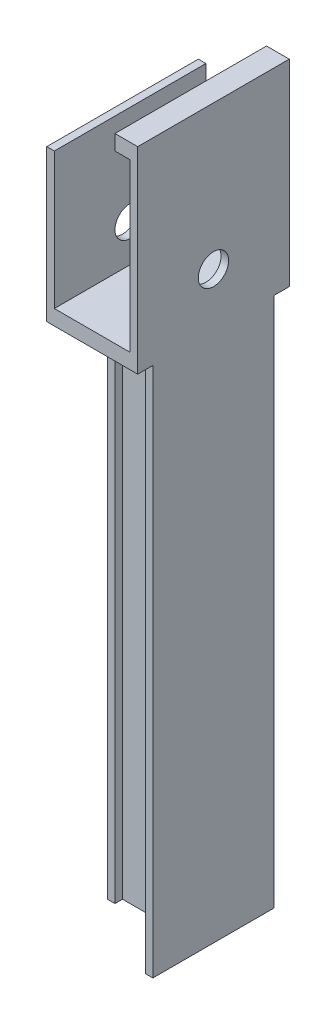
SolidWorks part; units mm, degrees
ref_plane "Front Plane" through (0, 0, 0) normal (0, 0, 1) x (1, 0, 0)
ref_plane "Top Plane" through (0, 0, 0) normal (0, 1, 0) x (1, 0, 0)
ref_plane "Right Plane" through (0, 0, 0) normal (1, 0, 0) x (0, 0, -1)
sketch "Sketch1" plane through (0, 0, 0) normal (0, 1, 0) x (1, 0, 0)
  line L1 (-130.7317, 99.2683) -> (-70.7317, 99.2683)
  line L2 (-130.7317, 99.2683) -> (-130.7317, -0.7317)
  line L3 (-130.7317, -0.7317) -> (-70.7317, -0.7317)
  line L4 (-70.7317, 99.2683) -> (-70.7317, -0.7317)
  dimension "D1" = 60
  dimension "D2" = 100
extrude "Boss-Extrude1" add sketch "Sketch1" along normal blind 100
sketch "Sketch2" plane through (0, 100, 0) normal (0, 1, 0) x (1, 0, 0)
  line L0 (-70.7317, 99.2683) -> (-130.7317, 99.2683) construction
  line L1 (-125.7317, 99.2683) -> (-75.7317, 99.2683)
  line L2 (-125.7317, 99.2683) -> (-125.7317, -0.7317)
  line L3 (-125.7317, -0.7317) -> (-75.7317, -0.7317)
  line L4 (-75.7317, 99.2683) -> (-75.7317, -0.7317)
  line L5 (-130.7317, -0.7317) -> (-70.7317, -0.7317) construction
  dimension "D1" = 50
  dimension "D2" = 5
extrude "Cut-Extrude1" cut sketch "Sketch2" against normal blind 40
sketch "Sketch3" plane through (0, 100, 0) normal (0, 1, 0) x (1, 0, 0)
  line L1 (-75.7317, 99.2683) -> (-70.7317, 99.2683)
  line L2 (-75.7317, 99.2683) -> (-75.7317, -0.7317)
  line L3 (-75.7317, -0.7317) -> (-70.7317, -0.7317)
  line L4 (-70.7317, 99.2683) -> (-70.7317, -0.7317)
extrude "Boss-Extrude2" add sketch "Sketch3" along normal blind 30
sketch "Sketch4" plane through (-75.7317, 0, 0) normal (-1, 0, 0) x (0, 0, 1)
  line L0 (0.7317, 60) -> (0.7317, 130) construction
  line L1 (-99.2683, 130) -> (0.7317, 130)
  line L2 (-99.2683, 130) -> (-99.2683, 120)
  line L3 (-99.2683, 120) -> (0.7317, 120)
  line L4 (0.7317, 130) -> (0.7317, 120)
  dimension "D1" = 10
extrude "Boss-Extrude3" add sketch "Sketch4" along normal blind 10
sketch "Sketch5" plane through (0, 0, 0) normal (0, -1, 0) x (-1, 0, 0)
  line L6 (70.7317, -0.7317) -> (70.7317, 99.2683) construction
  line L7 (70.7317, 89.2683) -> (130.7317, 89.2683)
  line L8 (70.7317, 89.2683) -> (70.7317, 9.2683)
  line L9 (70.7317, 9.2683) -> (130.7317, 9.2683)
  line L10 (130.7317, 89.2683) -> (130.7317, 9.2683)
  line L11 (130.7317, 99.2683) -> (130.7317, -0.7317) construction
  line L12 (70.7317, 99.2683) -> (130.7317, 99.2683) construction
  dimension "D1" = 10
  dimension "D2" = 80
extrude "Boss-Extrude4" add sketch "Sketch5" along normal blind 350
sketch "Sketch6" plane through (0, 60, 0) normal (0, 1, 0) x (1, 0, 0)
  line L1 (-125.7317, 99.2683) -> (-75.7317, 99.2683)
  line L2 (-125.7317, 99.2683) -> (-125.7317, -0.7317)
  line L3 (-125.7317, -0.7317) -> (-75.7317, -0.7317)
  line L4 (-75.7317, 99.2683) -> (-75.7317, -0.7317)
extrude "Cut-Extrude2" cut sketch "Sketch6" against normal blind 50
sketch "Sketch7" plane through (-130.7317, 0, 0) normal (-1, 0, 0) x (0, 0, 1)
  line L0 (0.7317, 100) -> (0.7317, 0) construction
  line L1 (-99.2683, 100) -> (0.7317, 100) construction
  circle A0 centre (-49.2683, 35) radius 10
  dimension "D1" = 50
  dimension "D2" = 65
extrude "Cut-Extrude3" cut sketch "Sketch7" against normal blind 80
sketch "Sketch8" plane through (0, -350, 0) normal (0, -1, 0) x (-1, 0, 0)
  line L0 (70.7317, 9.2683) -> (130.7317, 9.2683) construction
  line L1 (125.7317, 9.2683) -> (75.7317, 9.2683)
  line L2 (125.7317, 9.2683) -> (125.7317, 44.2683)
  line L3 (125.7317, 89.2683) -> (75.7317, 89.2683)
  line L4 (75.7317, 9.2683) -> (75.7317, 44.2683)
  line L5 (130.7317, 89.2683) -> (70.7317, 89.2683) construction
  line L6 (130.7317, 9.2683) -> (130.7317, 89.2683) construction
  line L7 (70.7317, 89.2683) -> (70.7317, 9.2683) construction
  line L8 (125.7317, 54.2683) -> (125.7317, 89.2683)
  line L9 (125.7317, 44.2683) -> (75.7317, 44.2683)
  line L11 (125.7317, 54.2683) -> (75.7317, 54.2683)
  line L13 (75.7317, 54.2683) -> (75.7317, 89.2683)
  dimension "D1" = 60
  dimension "D2" = 50
  dimension "D3" = 5
  dimension "D4" = 35
  dimension "D5" = 35
extrude "Cut-Extrude4" cut sketch "Sketch8" against normal blind 350
sketch "Sketch9" plane through (0, -350, 0) normal (0, -1, 0) x (-1, 0, 0)
  line L1 (125.7317, 54.2683) -> (125.7317, 89.2683) construction
  line L2 (125.7317, 59.2683) -> (130.7317, 59.2683)
  line L3 (125.7317, 59.2683) -> (125.7317, 89.2683)
  line L4 (125.7317, 89.2683) -> (130.7317, 89.2683)
  line L5 (130.7317, 59.2683) -> (130.7317, 89.2683)
  line L6 (125.7317, 9.2683) -> (125.7317, 44.2683) construction
  line L7 (125.7317, 39.2683) -> (130.7317, 39.2683)
  line L8 (125.7317, 39.2683) -> (125.7317, 9.2683)
  line L9 (125.7317, 9.2683) -> (130.7317, 9.2683)
  line L10 (130.7317, 39.2683) -> (130.7317, 9.2683)
  dimension "D1" = 30
  dimension "D2" = 30
extrude "Cut-Extrude5" cut sketch "Sketch9" against normal blind 350
